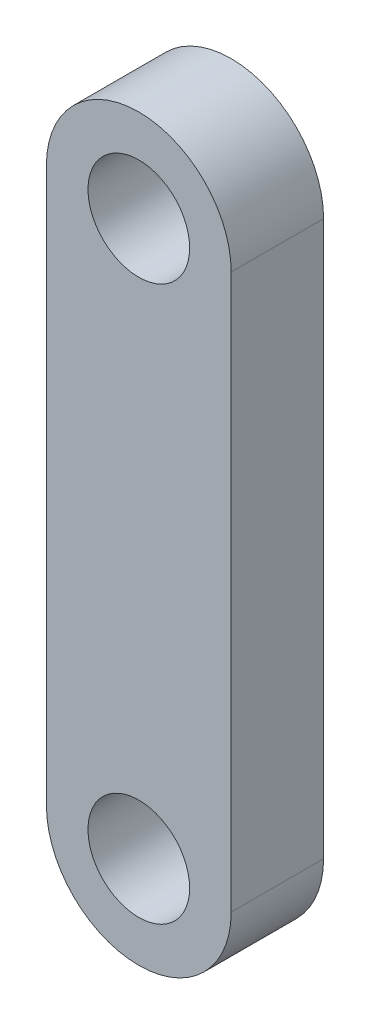
SolidWorks part; units mm, degrees
ref_plane "Front Plane" through (0, 0, 0) normal (0, 0, 1) x (1, 0, 0)
ref_plane "Top Plane" through (0, 0, 0) normal (0, 1, 0) x (1, 0, 0)
ref_plane "Right Plane" through (0, 0, 0) normal (1, 0, 0) x (0, 0, -1)
sketch "Sketch1" plane through (0, 0, 0) normal (0, 0, 1) x (1, 0, 0)
  line L0 (-2.54, 0) -> (2.54, 0) construction
  line L2 (2.54, -7.62) -> (2.54, 7.62)
  line L4 (-2.54, -7.62) -> (-2.54, 7.62)
  arc A0 (-2.54, 7.62) -> (2.54, 7.62) centre (0, 7.62) cw
  arc A1 (-2.54, -7.62) -> (2.54, -7.62) centre (0, -7.62) ccw
  circle A2 centre (0, -7.62) radius 1.397
  circle A3 centre (0, 7.62) radius 1.397
  point P0 (0, 0)
  dimension "D3" = 2.794
  dimension "D4" = 2.794
  dimension "D1" = 5.08
  dimension "D2" = 15.24
extrude "Boss-Extrude1" add sketch "Sketch1" along normal blind 2.54
